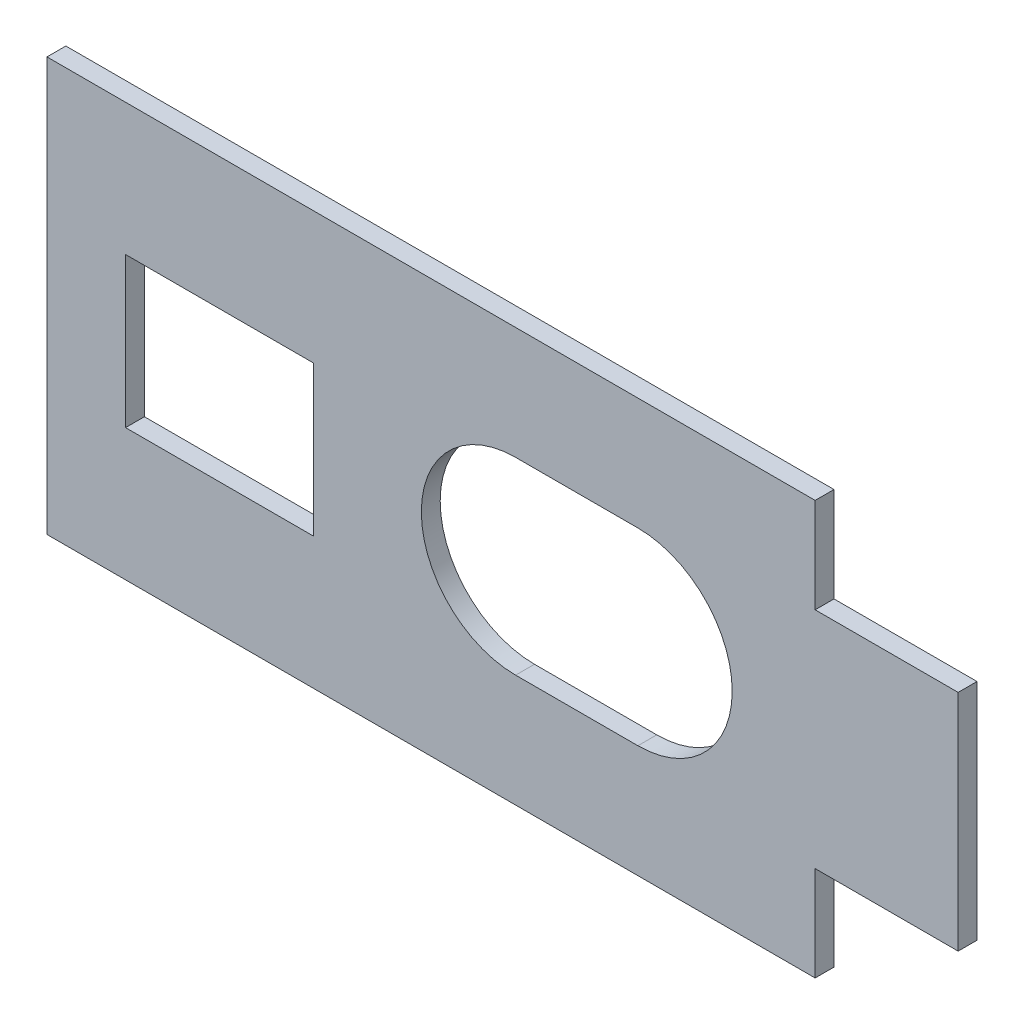
SolidWorks part; units mm, degrees
ref_plane "Front Plane" through (0, 0, 0) normal (0, 0, 1) x (1, 0, 0)
ref_plane "Top Plane" through (0, 0, 0) normal (0, 1, 0) x (1, 0, 0)
ref_plane "Right Plane" through (0, 0, 0) normal (1, 0, 0) x (0, 0, -1)
sketch "Sketch1" plane through (0, 0, 0.762) normal (0, 0, 1) x (1, 0, 0)
  line L0 (-6.0134, -30.2624) -> (-6.0134, -24.7125) construction
  line L1 (1.0732, -24.7125) -> (1.0732, -30.2624) construction
  line L2 (-6.0134, -24.5347) -> (-6.0134, -24.7125) construction
  line L3 (-6.0134, -30.2624) -> (-6.0134, -30.4402) construction
  line L4 (14.9416, -20.7184) -> (-14.9415, -20.7184) construction
  line L12 (-6.0134, -30.2624) -> (-6.0134, -24.7125) construction
  line L13 (-6.0134, -30.4402) -> (6.0135, -30.4402) construction
  line L14 (6.0135, -30.4402) -> (6.0135, -24.5347) construction
  line L15 (6.0135, -24.5347) -> (-6.0134, -24.5347) construction
  line L16 (-6.0134, -30.2624) -> (-6.0134, -24.7125) construction
  line L17 (1.0732, -24.7125) -> (1.0732, -30.2624) construction
  line L18 (-6.0134, -24.5347) -> (-6.0134, -24.7125) construction
  line L19 (-6.0134, -30.2624) -> (-6.0134, -30.4402) construction
  line L20 (-6.0134, -30.2624) -> (-6.0134, -24.7125) construction
  line L21 (-6.0134, -30.4402) -> (6.0135, -30.4402) construction
  line L22 (6.0135, -30.4402) -> (6.0135, -24.5347) construction
  line L23 (6.0135, -24.5347) -> (-6.0134, -24.5347) construction
  line L27 (-6.0134, -30.2624) -> (1.0732, -30.2624) construction
  line L28 (1.0732, -24.7125) -> (-6.0134, -24.7125) construction
  line L31 (-9.4424, -19.1309) -> (21.5953, -19.1309)
  line L32 (-9.4424, -19.1309) -> (-9.4424, -35.8441)
  line L33 (-9.4424, -35.8441) -> (21.5953, -35.8441)
  line L39 (21.5953, -19.1309) -> (21.5953, -22.9599)
  line L45 (27.3738, -22.9599) -> (27.3738, -32.015)
  line L46 (27.3738, -32.015) -> (21.5953, -32.015)
  line L47 (21.5953, -32.015) -> (21.5953, -35.8441)
  line L49 (14.4336, -27.4875) -> (9.4933, -27.4875) construction
  line L54 (14.4336, -31.2975) -> (9.4933, -31.2975)
  line L55 (14.4336, -23.6775) -> (9.4933, -23.6775)
  line L56 (1.0732, -30.2624) -> (6.0135, -30.2624) construction
  line L57 (1.0732, -24.7125) -> (-6.0134, -24.7125) construction
  line L58 (27.3738, -22.9599) -> (26.1038, -22.9599)
  line L59 (26.1038, -22.9599) -> (21.5953, -22.9599)
  line L60 (-6.0134, -30.2624) -> (1.0732, -30.2624) construction
  line L61 (-6.2674, -24.4585) -> (1.3272, -24.4585)
  line L62 (-6.2674, -24.4585) -> (-6.2674, -30.5164)
  line L63 (-6.2674, -30.5164) -> (1.3272, -30.5164)
  line L64 (1.3272, -24.4585) -> (1.3272, -30.5164)
  line L84 (28.0088, -22.9599) -> (28.0088, -32.015) construction
  line L85 (28.0088, -32.015) -> (32.5173, -32.015) construction
  line L86 (32.5173, -32.015) -> (32.5173, -22.9599) construction
  line L87 (32.5173, -22.9599) -> (28.0088, -22.9599) construction
  line L88 (28.0088, -22.9599) -> (28.0088, -32.015) construction
  line L89 (28.0088, -32.015) -> (32.5173, -32.015) construction
  line L90 (32.5173, -32.015) -> (32.5173, -22.9599)
  line L91 (32.5173, -22.9599) -> (28.0088, -22.9599) construction
  circle A0 centre (14.4336, -27.4875) radius 1.319 construction
  circle A1 centre (14.4336, -27.4875) radius 1.319 construction
  arc A2 (14.4336, -31.2975) -> (14.4336, -23.6775) centre (14.4336, -27.4875) ccw
  arc A3 (9.4933, -23.6775) -> (9.4933, -31.2975) centre (9.4933, -27.4875) ccw
  point P1 (27.3738, -27.4875)
  point P3 (-9.4424, -27.4875)
  point P28 (11.9634, -27.4875)
  point P38 (26.1038, -22.9599)
  point P45 (-2.4701, -24.4585)
  point P46 (-2.4701, -24.7125)
  point P47 (1.3272, -27.4875)
  point P48 (1.0732, -27.4875)
  line M91 (6.0135, -30.4402) -> (-6.0134, -30.4402)
  line M95 (-6.0134, -24.5347) -> (6.0135, -24.5347)
  line M96 (6.0135, -24.5347) -> (6.0135, -30.4402)
  line M97 (14.9416, -20.7184) -> (-14.9415, -20.7184)
  line M101 (-14.9415, -34.2566) -> (14.9416, -34.2566)
  arc M102 (14.9416, -34.2566) -> (17.4816, -31.7166) centre (14.9416, -31.7166) ccw
  line M103 (17.4816, -31.7166) -> (17.4816, -23.2584)
  arc M104 (17.4816, -23.2584) -> (14.9416, -20.7184) centre (14.9416, -23.2584) ccw
  dimension "D4" = 0.635
  dimension "D3" = 3.81
  dimension "D2" = 1.5875
  dimension "D5" = 1.27
  dimension "D7" = 0.254
  dimension "D8" = 0.254
  dimension "D1" = 3.175
extrude "Boss-Extrude2" add sketch "Sketch1" along normal blind 0.762 contours A2 L32 L33 L47 L46 L45 L58 L59 L39 L31 M103 M102 M101 M97 M104 | A3 L55 A2 L32 L54 L64 L63 L62 L61 M103 M104 M97 M101 M102 M96 M91 M95 | A3 L64 M96 M95 M91
